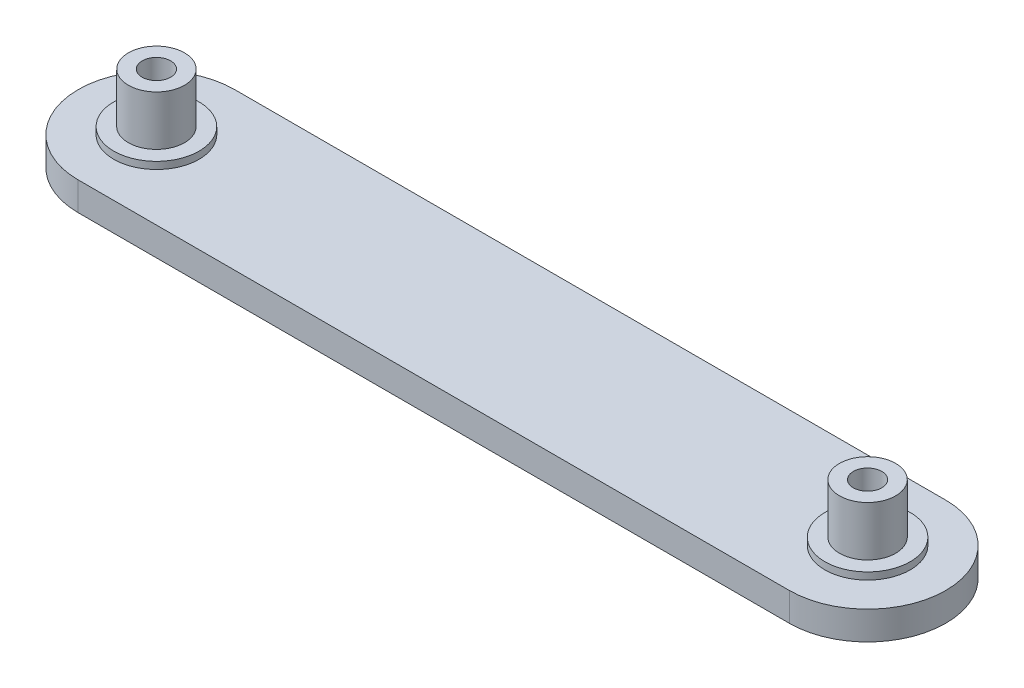
SolidWorks part; units mm, degrees
ref_plane "Front Plane" through (0, 0, 0) normal (0, 0, 1) x (1, 0, 0)
ref_plane "Top Plane" through (0, 0, 0) normal (0, 1, 0) x (1, 0, 0)
ref_plane "Right Plane" through (0, 0, 0) normal (1, 0, 0) x (0, 0, -1)
sketch "Sketch1" plane through (0, 0, 0) normal (0, 1, 0) x (1, 0, 0)
  line L0 (0, 0) -> (100, 0) construction
  line L1 (0, 11) -> (100, 11)
  line L2 (0, -11) -> (100, -11)
  arc A0 (0, 11) -> (0, -11) centre (0, 0) ccw
  arc A1 (100, -11) -> (100, 11) centre (100, 0) ccw
  point P3 (50, 0)
  dimension "D2" = 11
  dimension "D1" = 100
extrude "Boss-Extrude1" add sketch "Sketch1" along normal blind 4
sketch "Sketch2" plane through (0, 4, 0) normal (0, 1, 0) x (1, 0, 0)
  circle A0 centre (0, 0) radius 6
  arc A1 (100, -11) -> (100, 11) centre (100, 0) ccw construction
  arc A2 (100, -11) -> (100, 11) centre (100, 0) ccw construction
  circle A3 centre (100, 0) radius 6
  dimension "D1" = 12
extrude "Boss-Extrude2" add sketch "Sketch2" along normal blind 1 contours A0
sketch "Sketch3" plane through (0, 5, 0) normal (0, 1, 0) x (1, 0, 0)
  circle A0 centre (0, 0) radius 3.95
  circle A1 centre (100, 0) radius 3.95
  circle A2 centre (100, 0) radius 6
  circle A3 centre (100, 0) radius 6 construction
  dimension "D2" = 7.9
  dimension "D1" = 0
extrude "Boss-Extrude3" add sketch "Sketch3" along normal blind 7
sketch "Sketch4" plane through (0, 12, 0) normal (0, 1, 0) x (1, 0, 0)
  circle A0 centre (0, 0) radius 2
  circle A1 centre (100, 0) radius 2
  circle A2 centre (100, 0) radius 3.95
  circle A3 centre (100, 0) radius 3.95 construction
  dimension "D2" = 4
  dimension "D1" = 0
extrude "Cut-Extrude1" cut sketch "Sketch4" against normal through all
